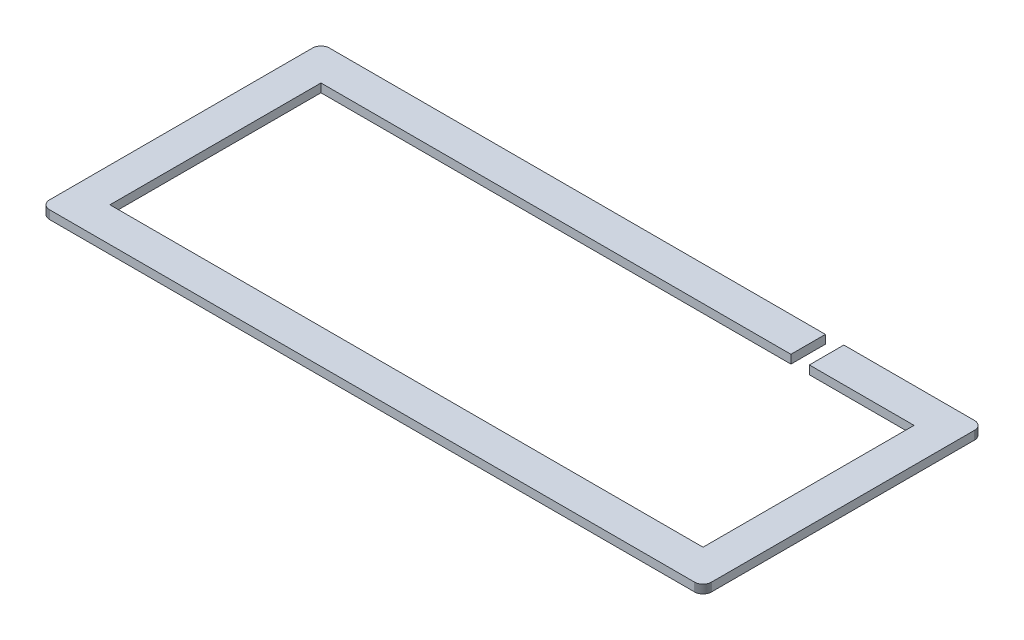
SolidWorks part; units mm, degrees
ref_plane "Front Plane" through (0, 0, 0) normal (0, 0, 1) x (1, 0, 0)
ref_plane "Top Plane" through (0, 0, 0) normal (0, 1, 0) x (1, 0, 0)
ref_plane "Right Plane" through (0, 0, 0) normal (1, 0, 0) x (0, 0, -1)
sketch "Sketch1" plane through (0, 0, 0) normal (0, 1, 0) x (1, 0, 0)
  line L0 (295.626, 164.299) -> (295.626, 144.099)
  line L1 (295.626, 144.099) -> (20.2944, 144.099)
  line L2 (20.2944, 144.099) -> (20.2944, 20.4735)
  line L3 (20.2944, 20.4735) -> (367.757, 20.4735)
  line L4 (367.757, 20.4735) -> (367.757, 144.099)
  line L5 (367.757, 144.099) -> (306.426, 144.099)
  line L6 (306.426, 144.099) -> (306.426, 164.299)
  line L7 (306.426, 164.299) -> (382.958, 164.299)
  line L8 (382.958, 164.299) -> (383.35, 164.284)
  line L9 (383.35, 164.284) -> (383.741, 164.237)
  line L10 (383.741, 164.237) -> (384.126, 164.162)
  line L11 (384.126, 164.162) -> (384.503, 164.055)
  line L12 (384.503, 164.055) -> (384.87, 163.919)
  line L13 (384.87, 163.919) -> (385.226, 163.755)
  line L14 (385.226, 163.755) -> (385.572, 163.564)
  line L15 (385.572, 163.564) -> (385.897, 163.344)
  line L16 (385.897, 163.344) -> (386.203, 163.102)
  line L17 (386.203, 163.102) -> (386.493, 162.834)
  line L18 (386.493, 162.834) -> (386.761, 162.547)
  line L19 (386.761, 162.547) -> (387.004, 162.238)
  line L20 (387.004, 162.238) -> (387.223, 161.913)
  line L21 (387.223, 161.913) -> (387.414, 161.569)
  line L22 (387.414, 161.569) -> (387.576, 161.212)
  line L23 (387.576, 161.212) -> (387.713, 160.845)
  line L24 (387.713, 160.845) -> (387.819, 160.467)
  line L25 (387.819, 160.467) -> (387.897, 160.082)
  line L26 (387.897, 160.082) -> (387.943, 159.693)
  line L27 (387.943, 159.693) -> (387.96, 159.299)
  line L28 (387.96, 159.299) -> (387.96, 5.2724)
  line L29 (387.96, 5.2724) -> (387.943, 4.881)
  line L30 (387.943, 4.881) -> (387.897, 4.491)
  line L31 (387.897, 4.491) -> (387.819, 4.1066)
  line L32 (387.819, 4.1066) -> (387.713, 3.7276)
  line L33 (387.713, 3.7276) -> (387.576, 3.3597)
  line L34 (387.576, 3.3597) -> (387.414, 3.0041)
  line L35 (387.414, 3.0041) -> (387.223, 2.661)
  line L36 (387.223, 2.661) -> (387.004, 2.3344)
  line L37 (387.004, 2.3344) -> (386.761, 2.0257)
  line L38 (386.761, 2.0257) -> (386.493, 1.7377)
  line L39 (386.493, 1.7377) -> (386.203, 1.4704)
  line L40 (386.203, 1.4704) -> (385.897, 1.2278)
  line L41 (385.897, 1.2278) -> (385.572, 1.0101)
  line L42 (385.572, 1.0101) -> (385.226, 0.8186)
  line L43 (385.226, 0.8186) -> (384.87, 0.6546)
  line L44 (384.87, 0.6546) -> (384.503, 0.5181)
  line L45 (384.503, 0.5181) -> (384.126, 0.412)
  line L46 (384.126, 0.412) -> (383.741, 0.3349)
  line L47 (383.741, 0.3349) -> (383.35, 0.2894)
  line L48 (383.35, 0.2894) -> (382.958, 0.2729)
  line L49 (382.958, 0.2729) -> (5.096, 0.2729)
  line L50 (5.096, 0.2729) -> (4.7019, 0.2894)
  line L51 (4.7019, 0.2894) -> (4.3119, 0.3349)
  line L52 (4.3119, 0.3349) -> (3.9274, 0.412)
  line L53 (3.9274, 0.412) -> (3.5498, 0.5181)
  line L54 (3.5498, 0.5181) -> (3.1819, 0.6546)
  line L55 (3.1819, 0.6546) -> (2.825, 0.8186)
  line L56 (2.825, 0.8186) -> (2.4819, 1.0101)
  line L57 (2.4819, 1.0101) -> (2.1566, 1.2278)
  line L58 (2.1566, 1.2278) -> (1.848, 1.4704)
  line L59 (1.848, 1.4704) -> (1.5599, 1.7377)
  line L60 (1.5599, 1.7377) -> (1.2926, 2.0257)
  line L61 (1.2926, 2.0257) -> (1.0501, 2.3344)
  line L62 (1.0501, 2.3344) -> (0.831, 2.661)
  line L63 (0.831, 2.661) -> (0.6394, 3.0041)
  line L64 (0.6394, 3.0041) -> (0.4754, 3.3597)
  line L65 (0.4754, 3.3597) -> (0.339, 3.7276)
  line L66 (0.339, 3.7276) -> (0.2329, 4.1066)
  line L67 (0.2329, 4.1066) -> (0.1571, 4.491)
  line L68 (0.1571, 4.491) -> (0.1102, 4.881)
  line L69 (0.1102, 4.881) -> (0.0951, 5.2737)
  line L70 (0.0951, 5.2737) -> (0.0951, 159.299)
  line L71 (0.0951, 159.299) -> (0.1102, 159.693)
  line L72 (0.1102, 159.693) -> (0.1571, 160.082)
  line L73 (0.1571, 160.082) -> (0.2329, 160.467)
  line L74 (0.2329, 160.467) -> (0.339, 160.845)
  line L75 (0.339, 160.845) -> (0.4754, 161.212)
  line L76 (0.4754, 161.212) -> (0.6394, 161.569)
  line L77 (0.6394, 161.569) -> (0.831, 161.913)
  line L78 (0.831, 161.913) -> (1.0501, 162.238)
  line L79 (1.0501, 162.238) -> (1.2926, 162.547)
  line L80 (1.2926, 162.547) -> (1.5599, 162.834)
  line L81 (1.5599, 162.834) -> (1.848, 163.102)
  line L82 (1.848, 163.102) -> (2.1566, 163.344)
  line L83 (2.1566, 163.344) -> (2.4819, 163.564)
  line L84 (2.4819, 163.564) -> (2.825, 163.755)
  line L85 (2.825, 163.755) -> (3.1819, 163.919)
  line L86 (3.1819, 163.919) -> (3.5498, 164.055)
  line L87 (3.5498, 164.055) -> (3.9274, 164.162)
  line L88 (3.9274, 164.162) -> (4.3119, 164.237)
  line L89 (4.3119, 164.237) -> (4.7019, 164.284)
  line L90 (4.7019, 164.284) -> (5.096, 164.299)
  line L91 (5.096, 164.299) -> (295.626, 164.299)
extrude "Boss-Extrude1" add sketch "Sketch1" along normal blind 5
